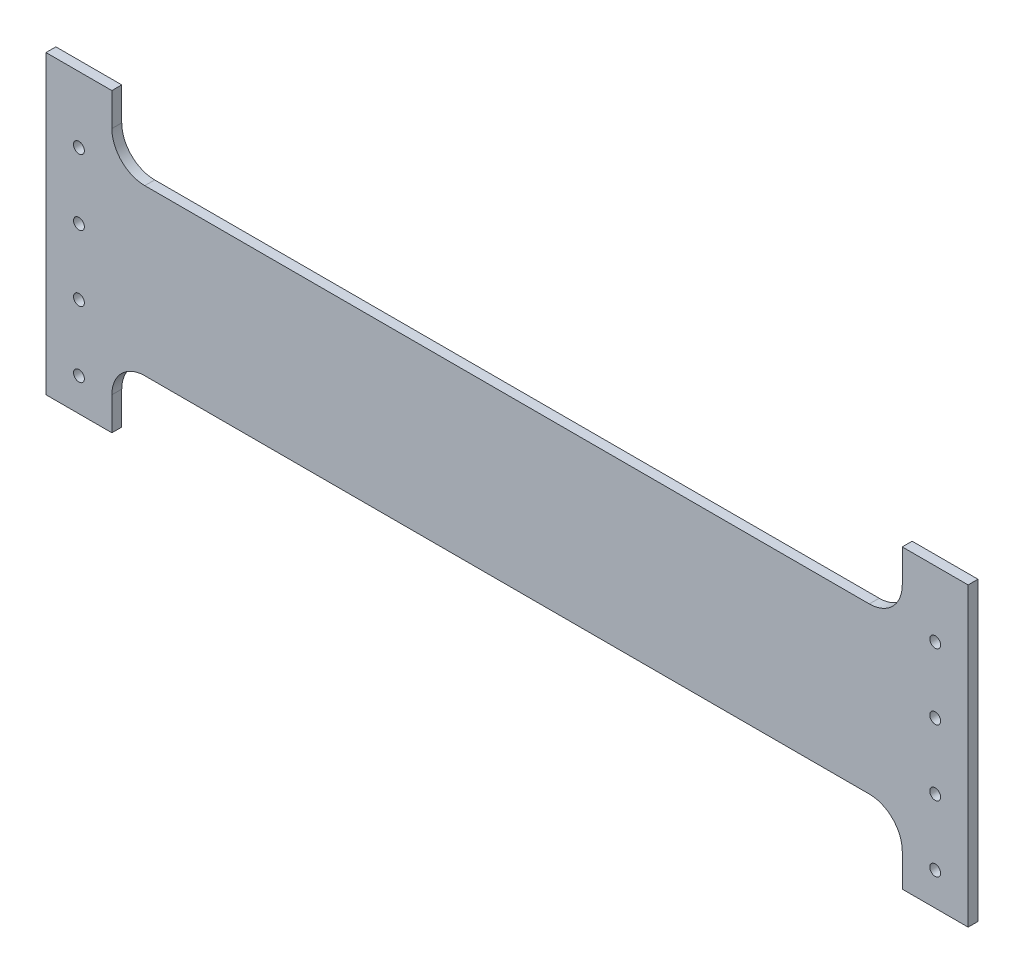
SolidWorks part; units mm, degrees
ref_plane "前视基准面" through (0, 0, 0) normal (0, 0, 1) x (1, 0, 0)
ref_plane "上视基准面" through (0, 0, 0) normal (0, 1, 0) x (1, 0, 0)
ref_plane "右视基准面" through (0, 0, 0) normal (1, 0, 0) x (0, 0, -1)
other "Configuration Table"
sketch "草图1" plane through (0, 0, 0) normal (0, 0, 1) x (1, 0, 0)
  line L0 (0, 0) -> (141.7945, 0) construction
  line L1 (-110, 25) -> (110, 25)
  line L3 (-110, -25) -> (110, -25)
  line L5 (-120, 25) -> (120, -25) construction
  line L6 (-120, -25) -> (120, 25) construction
  line L7 (0, 0) -> (0, 68.1415) construction
  line L8 (-120, -45) -> (-120, -35)
  line L9 (-120, 45) -> (-140, 45)
  line L10 (-140, 45) -> (-140, -45)
  line L11 (120, 45) -> (140, 45)
  line L12 (120, -45) -> (120, -35)
  line L13 (140, 45) -> (140, -45)
  line L14 (120, -45) -> (140, -45)
  line L15 (-120, -45) -> (-140, -45)
  line L16 (-120, 35) -> (-120, 45)
  line L17 (120, 35) -> (120, 45)
  line L18 (-130, 45) -> (-130, -45) construction
  arc A0 (120, -35) -> (110, -25) centre (110, -35) ccw
  arc A1 (120, 35) -> (110, 25) centre (110, 35) cw
  arc A2 (-120, -35) -> (-110, -25) centre (-110, -35) cw
  arc A3 (-110, 25) -> (-120, 35) centre (-110, 35) cw
  circle A4 centre (-130, 25) radius 1.65
  circle A5 centre (-130, 5) radius 1.65
  circle A6 centre (-130, -15) radius 1.65
  circle A7 centre (-130, -35) radius 1.65
  circle A8 centre (130, -35) radius 1.65
  circle A9 centre (130, -15) radius 1.65
  circle A10 centre (130, 5) radius 1.65
  circle A11 centre (130, 25) radius 1.65
  point P0 (0, 0)
  point P18 (140, 0)
  point P20 (-141.7945, 0)
  point P21 (-140, 0)
  dimension "D5" = 10
  dimension "D6" = 3.3
  dimension "D1" = 240
  dimension "D2" = 50
  dimension "D3" = 20
  dimension "D4" = 50
  dimension "D7" = 20
  dimension "D8" = 4
extrude "凸台-拉伸1" add sketch "草图1" along normal blind 3
